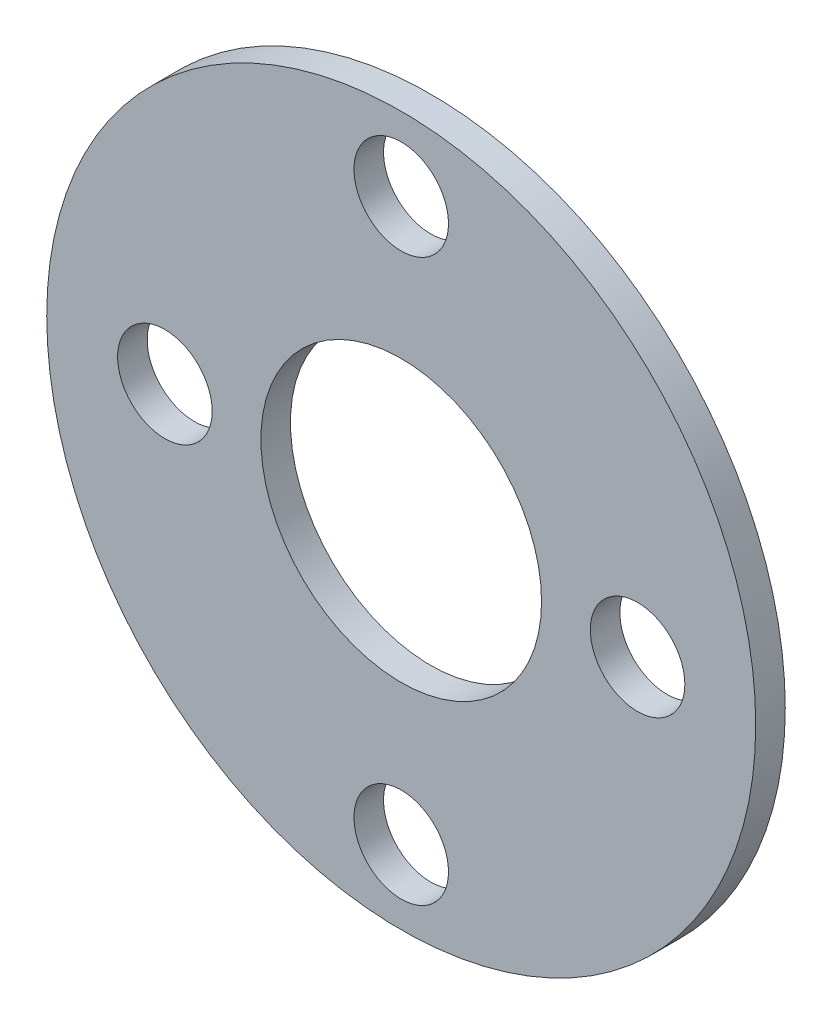
SolidWorks part; units mm, degrees
material "A-玻璃纤维"
ref_plane "前视基准面" through (0, 0, 0) normal (0, 0, 1) x (1, 0, 0)
ref_plane "上视基准面" through (0, 0, 0) normal (0, 1, 0) x (1, 0, 0)
ref_plane "右视基准面" through (0, 0, 0) normal (1, 0, 0) x (0, 0, -1)
sketch "草图1" plane through (0, 0, 0) normal (0, 0, 1) x (1, 0, 0)
  circle A0 centre (0, 0) radius 12
  circle A1 centre (0, 0) radius 4.75
  circle A2 centre (8, 0) radius 1.6
  circle A3 centre (-8, 0) radius 1.6
  circle A4 centre (0, 9.5) radius 1.6
  circle A5 centre (0, -9.5) radius 1.6
  dimension "D1" = 24
  dimension "D2" = 9.5
  dimension "D3" = 3.2
  dimension "D4" = 16
  dimension "D5" = 8
  dimension "D6" = 19
  dimension "D7" = 9.5
extrude "凸台-拉伸1" add sketch "草图1" along normal blind 1
